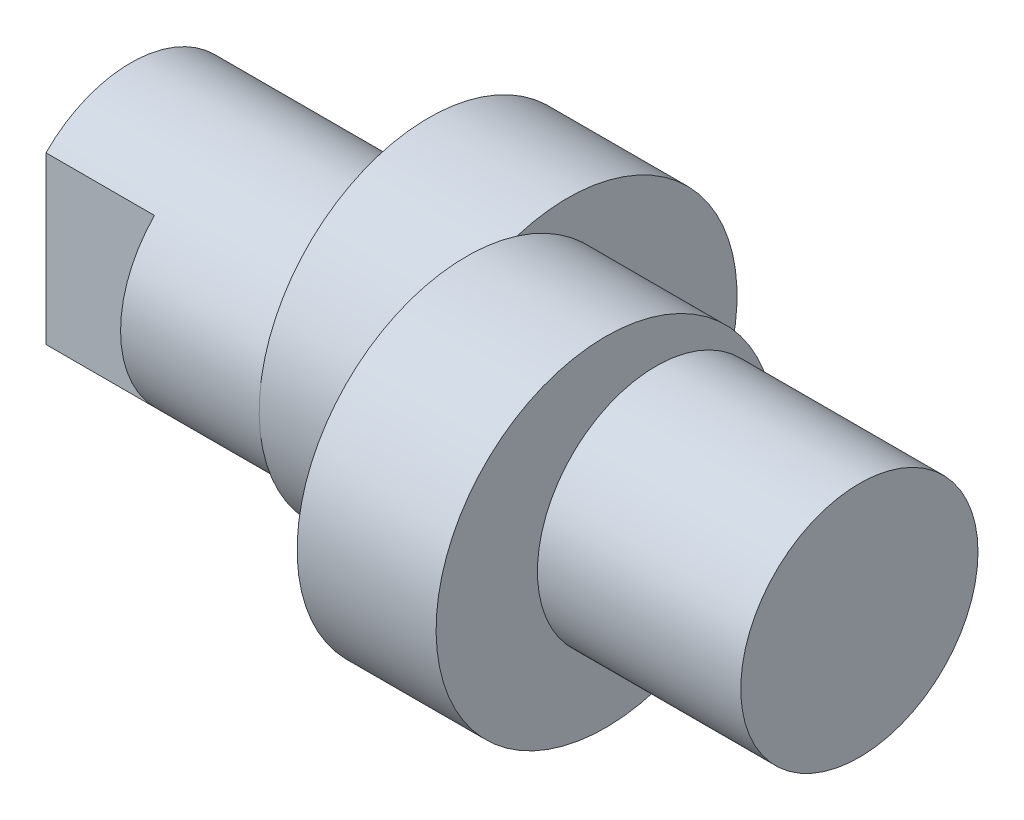
SolidWorks part; units mm, degrees
ref_plane "前视基准面" through (0, 0, 0) normal (0, 0, 1) x (1, 0, 0)
ref_plane "上视基准面" through (0, 0, 0) normal (0, 1, 0) x (1, 0, 0)
ref_plane "右视基准面" through (0, 0, 0) normal (1, 0, 0) x (0, 0, -1)
sketch "草图1" plane through (0, 0, 0) normal (1, 0, 0) x (0, 0, -1)
  line L0 (0, 0) -> (1.5, 0)
  circle A0 centre (0, 0) radius 3.5
  circle A1 centre (1.5, 0) radius 5
  dimension "D1" = 7
  dimension "D3" = 10
  dimension "D2" = 1.5
extrude "凸台-拉伸1" add sketch "草图1" against normal blind 7.3
sketch "草图2" plane through (0, 0, 0) normal (1, 0, 0) x (0, 0, -1)
  line L0 (0, 0) -> (1.49, 0)
  circle A0 centre (1.49, 0) radius 5
  circle A1 centre (0, 0) radius 3.5
  circle A2 centre (0, 0) radius 3.5
  dimension "D3" = 10
  dimension "D2" = 1.49
  dimension "D1" = 0
extrude "凸台-拉伸2" add sketch "草图2" along normal blind 4.1 contours A0
sketch "草图3" plane through (4.1, 0, 0) normal (1, 0, 0) x (0, 0, -1)
  line L0 (0, 0) -> (-1.49, 0)
  circle A0 centre (-1.49, 0) radius 5
  dimension "D2" = 10
  dimension "D1" = 1.49
extrude "凸台-拉伸3" add sketch "草图3" along normal blind 4.1 contours A0
sketch "草图4" plane through (8.2, 0, 0) normal (1, 0, 0) x (0, 0, -1)
  circle A0 centre (0, 0) radius 3.5
  dimension "D1" = 7
extrude "凸台-拉伸4" add sketch "草图4" along normal blind 6
sketch "草图7" plane through (-7.3, 0, 0) normal (-1, 0, 0) x (0, 0, 1)
  line L0 (-3.5, 0) -> (-2.5, 0)
  line L1 (3.5, 0) -> (2.5, 0)
  line L2 (-2.5, 0) -> (-2.5, -2.4495)
  line L3 (-2.5, 0) -> (-2.5, 2.4495)
  line L4 (2.5, 0) -> (2.5, -2.4495)
  line L5 (2.5, 0) -> (2.5, 2.4495)
  circle A0 centre (0, 0) radius 3.5 construction
  circle A1 centre (0, 0) radius 3.5 construction
  circle A3 centre (0, 0) radius 3.5
  circle M4 centre (0, 0) radius 3.5
  dimension "D1" = 1
  dimension "D2" = 1
extrude "切除-拉伸1" cut sketch "草图7" against normal blind 3.2 contours L2 L0 M4 | L0 L3 M4 | L1 L4 M4 | L5 L1 M4
